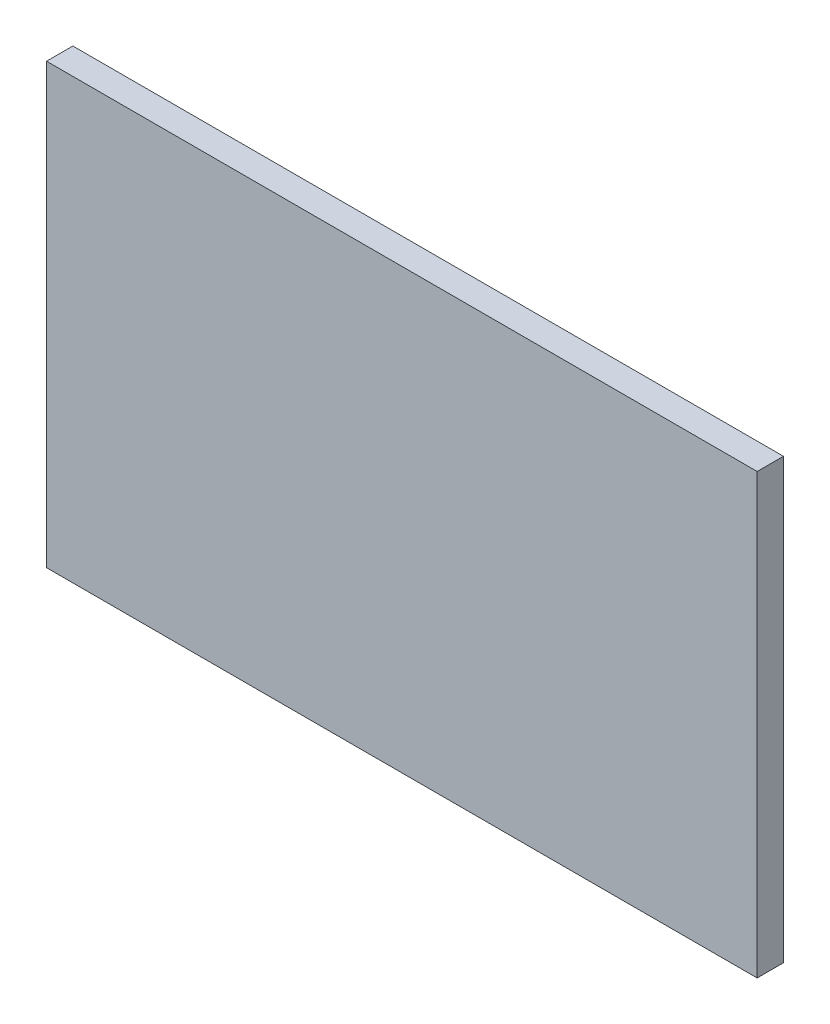
SolidWorks part; units mm, degrees
ref_plane "Plan de face" through (0, 0, 0) normal (0, 0, 1) x (1, 0, 0)
ref_plane "Plan de dessus" through (0, 0, 0) normal (0, 1, 0) x (1, 0, 0)
ref_plane "Plan de droite" through (0, 0, 0) normal (1, 0, 0) x (0, 0, -1)
sketch "Esquisse1" plane through (0, 0, 0) normal (0, 0, 1) x (1, 0, 0)
  line L0 (-1, 0.6674) -> (26, 0.6674)
  line L1 (26, 0.6674) -> (26, -16)
  line L2 (26, -16) -> (-1, -16)
  line L3 (-1, -16) -> (-1, 0.6674)
extrude "Component_Outline" add sketch "Esquisse1" along normal blind 1 separate body
sketch3d "Esquisse3D1"
  line L0 (0, 0, 0) -> (1, 0, 0)
  line L1 (0, 0, 0) -> (0, 1, 0)
  line L2 (0, 0, 0) -> (0, 0, 1)
  point P0 (0, 0, 0)
